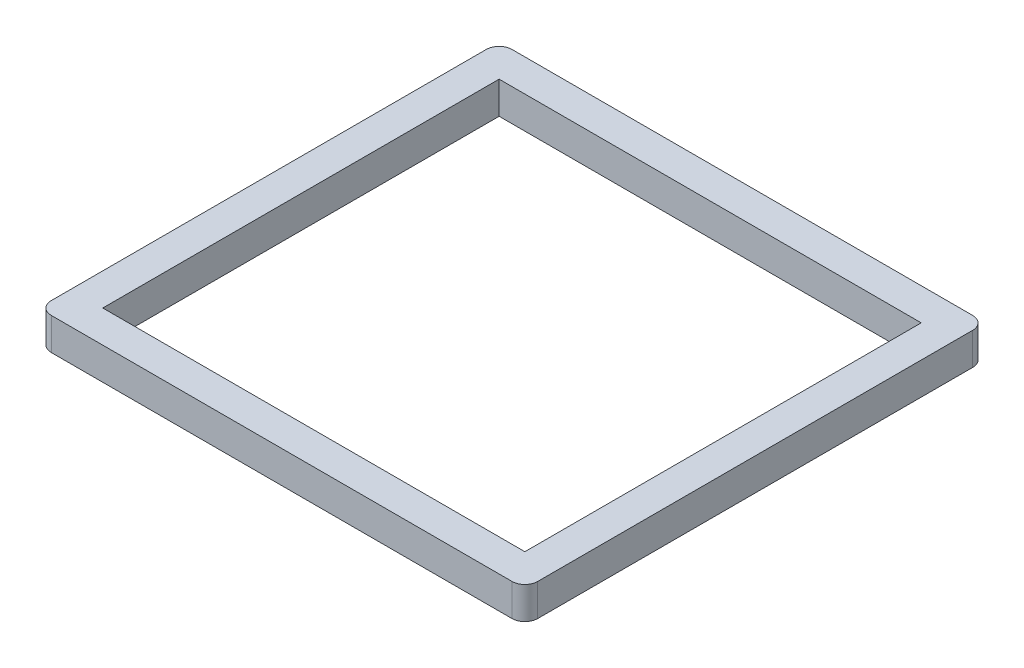
SolidWorks part; units mm, degrees
ref_plane "Front Plane" through (0, 0, 0) normal (0, 0, 1) x (1, 0, 0)
ref_plane "Top Plane" through (0, 0, 0) normal (0, 1, 0) x (1, 0, 0)
ref_plane "Right Plane" through (0, 0, 0) normal (1, 0, 0) x (0, 0, -1)
sketch "Sketch1" plane through (0, 0, 0) normal (0, 1, 0) x (1, 0, 0)
  line L1 (-41.656, 39.116) -> (41.656, 39.116)
  line L2 (-41.656, 39.116) -> (-41.656, -39.116)
  line L3 (-41.656, -39.116) -> (41.656, -39.116)
  line L4 (41.656, 39.116) -> (41.656, -39.116)
  line L5 (-45.466, 45.466) -> (45.466, 45.466)
  line L6 (-48.006, 42.926) -> (-48.006, -42.926)
  line L7 (-45.466, -45.466) -> (45.466, -45.466)
  line L8 (48.006, 42.926) -> (48.006, -42.926)
  arc A0 (-48.006, -42.926) -> (-45.466, -45.466) centre (-45.466, -42.926) ccw
  arc A1 (45.466, -45.466) -> (48.006, -42.926) centre (45.466, -42.926) ccw
  arc A2 (45.466, 45.466) -> (48.006, 42.926) centre (45.466, 42.926) cw
  arc A3 (-45.466, 45.466) -> (-48.006, 42.926) centre (-45.466, 42.926) ccw
  point P4 (0, 39.116)
  point P6 (-41.656, 0)
  dimension "D7" = 2.54
  dimension "D1" = 83.312
  dimension "D2" = 78.232
  dimension "D3" = 6.35
  dimension "D4" = 6.35
  dimension "D5" = 6.35
  dimension "D6" = 6.35
extrude "Boss-Extrude1" add sketch "Sketch1" along normal blind 6.35
